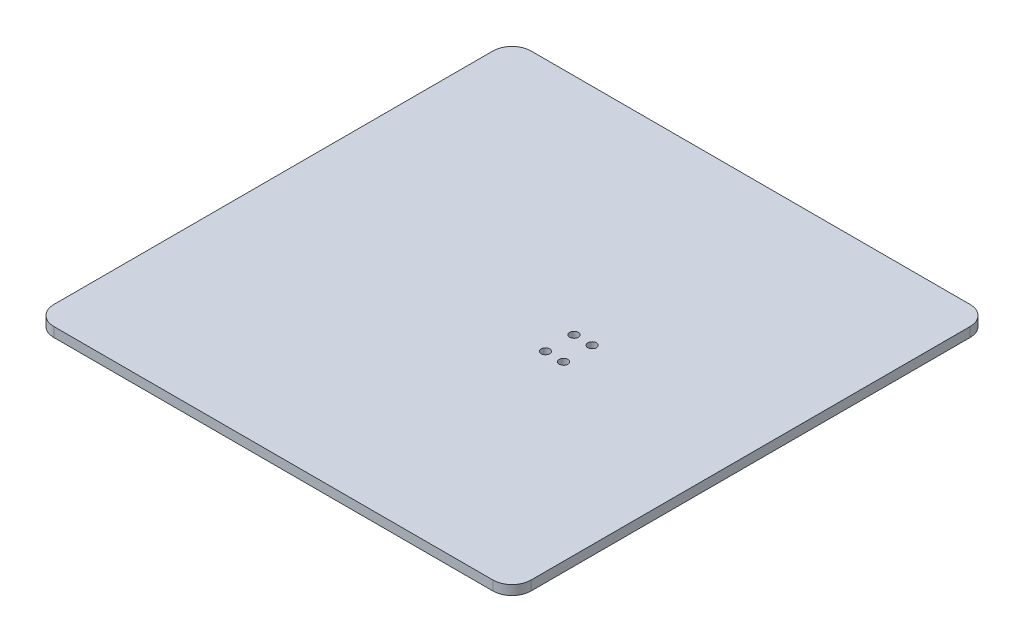
SolidWorks part; units mm, degrees
ref_plane "Alzado" through (0, 0, 0) normal (0, 0, 1) x (1, 0, 0)
ref_plane "Planta" through (0, 0, 0) normal (0, 1, 0) x (1, 0, 0)
ref_plane "Vista lateral" through (0, 0, 0) normal (1, 0, 0) x (0, 0, -1)
sketch "Croquis1" plane through (0, 0, 0) normal (0, 1, 0) x (1, 0, 0)
  line L1 (-230, 250) -> (230, 250)
  line L2 (-250, 230) -> (-250, -230)
  line L3 (-230, -250) -> (230, -250)
  line L4 (250, 230) -> (250, -230)
  line L15 (-225, 123.755) -> (225, 123.755) construction
  line L16 (-225, 123.755) -> (-225, -123.755) construction
  line L17 (-225, -123.755) -> (225, -123.755) construction
  line L18 (225, 123.755) -> (225, -123.755) construction
  arc A0 (250, -230) -> (230, -250) centre (230, -230) cw
  arc A1 (250, 230) -> (230, 250) centre (230, 230) ccw
  arc A2 (-230, 250) -> (-250, 230) centre (-230, 230) ccw
  arc A3 (-230, -250) -> (-250, -230) centre (-230, -230) cw
  point P1 (0, 0)
  point P2 (225, 0)
  point P3 (0, 123.755)
  point P5 (0, 250)
  point P18 (0, 0)
  point P23 (-250, 0)
  dimension "D3" = 20
  dimension "D1" = 500
  dimension "D2" = 500
  dimension "D4" = 450
  dimension "D5" = 247.51
extrude "Saliente-Extruir1" add sketch "Croquis1" along normal blind 10
sketch "Croquis4" plane through (0, 10, 0) normal (0, 1, 0) x (1, 0, 0)
  arc A0 (69, 19.5) -> (69, 10.5) centre (69, 15) ccw construction
  arc A1 (50, 19.5) -> (50, 10.5) centre (50, 15) ccw construction
  arc A2 (50, -10.5) -> (50, -19.5) centre (50, -15) ccw construction
  arc A3 (69, -10.5) -> (69, -19.5) centre (69, -15) ccw construction
  arc A4 (69, 19.5) -> (69, 10.5) centre (69, 15) ccw
  arc A5 (50, 19.5) -> (50, 10.5) centre (50, 15) ccw
  arc A6 (50, -10.5) -> (50, -19.5) centre (50, -15) ccw
  arc A7 (69, -10.5) -> (69, -19.5) centre (69, -15) ccw
  circle A8 centre (69, -15) radius 4.5
  circle A9 centre (50, -15) radius 4.5
  circle A10 centre (50, 15) radius 4.5
  circle A11 centre (69, 15) radius 4.5
extrude "Cortar-Extruir2" cut sketch "Croquis4" against normal through all contours A7 A8 | A6 A9 | A5 A10 | A4 A11
